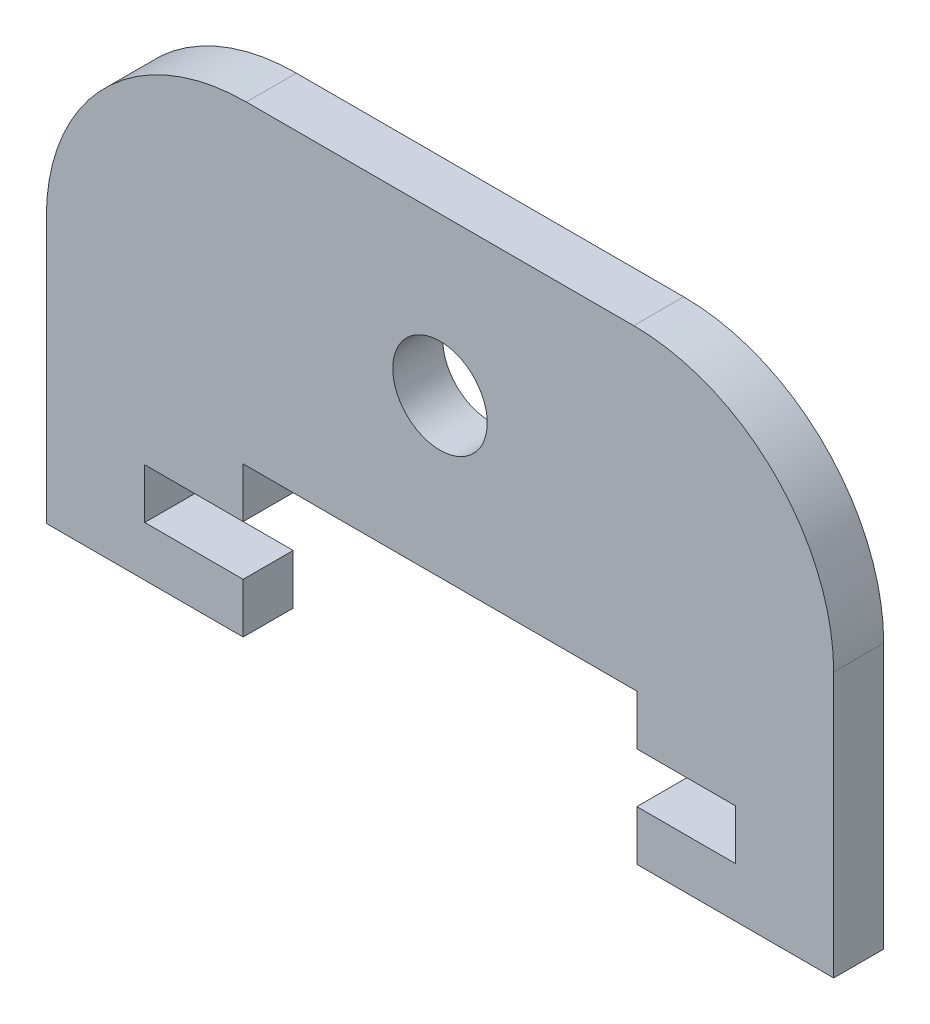
SolidWorks part; units mm, degrees
ref_plane "Front Plane" through (0, 0, 0) normal (0, 0, 1) x (1, 0, 0)
ref_plane "Top Plane" through (0, 0, 0) normal (0, 1, 0) x (1, 0, 0)
ref_plane "Right Plane" through (0, 0, 0) normal (1, 0, 0) x (0, 0, -1)
sketch "Sketch1" plane through (0, 0, 0) normal (0, 0, 1) x (1, 0, 0)
  line L0 (50, 40) -> (50, -11.8795) construction
  line L1 (25, 0) -> (75, 0)
  line L2 (0, 0) -> (0, 40)
  line L3 (0, 40) -> (100, 40)
  line L4 (100, 0) -> (100, 40)
  line L6 (0, 0) -> (0, -6.35)
  line L8 (25, 0) -> (25, -6.35)
  line L9 (75, 0) -> (75, -6.35)
  line L11 (100, 0) -> (100, -6.35)
  line L12 (0, -6.35) -> (0, -19.05)
  line L13 (0, -19.05) -> (25, -19.05)
  line L14 (25, -19.05) -> (25, -6.35)
  line L15 (75, -19.05) -> (75, -6.35)
  line L16 (100, -19.05) -> (75, -19.05)
  line L17 (100, -6.35) -> (100, -19.05)
  dimension "D1" = 100
  dimension "D2" = 6.35
  dimension "D3" = 40
  dimension "D4" = 25
  dimension "D5" = 6.35
  dimension "D6" = 12.7
extrude "Boss-Extrude1" add sketch "Sketch1" along normal blind 6.35
sketch "Sketch2" plane through (0, 0, 6.35) normal (0, 0, 1) x (1, 0, 0)
  line L0 (-10.2656, 2) -> (76.84, 2) construction
  line L2 (50, 40) -> (50, 0) construction
  line L3 (100, 40) -> (0, 40) construction
  line L4 (25, 0) -> (75, 0) construction
  circle A0 centre (50, 20) radius 6
  dimension "D3" = 12
  dimension "D1" = 20
extrude "Cut-Extrude1" cut sketch "Sketch2" against normal through all both and the other way through all
fillet "Fillet1" radius 25.4 2 edges at (100, 40, 3.175) (0, 40, 3.175)
sketch "Sketch3" plane through (0, 0, 6.35) normal (0, 0, 1) x (1, 0, 0)
  line L0 (50.038, 52.1218) -> (50.038, -31.1869) construction
  line L1 (75, -6.35) -> (87.5, -6.35)
  line L2 (25, 0) -> (25, -6.35) construction
  line L3 (25, -19.05) -> (25, 0) construction
  line L4 (25, -6.35) -> (12.5, -6.35)
  line L5 (12.5, -6.35) -> (12.5, -12.7)
  line L6 (12.5, -12.7) -> (25, -12.7)
  line L7 (25, -6.35) -> (25, -12.7)
  line L10 (75, 0) -> (75, -19.05) construction
  line L11 (87.5, -6.35) -> (87.5, -12.7)
  line L12 (87.5, -12.7) -> (75, -12.7)
  line L13 (75, -6.35) -> (75, -12.7)
  line L14 (25, 0) -> (75, 0) construction
  dimension "D5" = 6.35
  dimension "D1" = 6.35
  dimension "D2" = 12.5
  dimension "D3" = 6.35
  dimension "D4" = 50.038
  dimension "D6" = 6.35
  dimension "D7" = 12.5
extrude "Cut-Extrude2" cut sketch "Sketch3" against normal through all both and the other way through all
equation "\"Wheel Thickness\"= 1in"
equation "\"Wheel Diameter\"= 3in"
equation "\"Motor Rear Diameter\" = 36.2mm"
equation "\"Motor Front Diameter\" = 12mm"
equation "\"Material Thickness\" = .25in"
equation "\"Wheel Cutout Diameter\"= 2cm"
equation "\"Motor Mount Tab Thickness\" = 100mm"
equation "\"Motor Mount Tab Height\" = 40mm"
equation "\"D1@Sketch1\"=\"Motor Mount Tab Thickness\""
equation "\"D1@Boss-Extrude1\"=\"Material Thickness\""
equation "\"D2@Sketch1\"=\"Material Thickness\""
equation "\"D3@Sketch1\"=\"Motor Mount Tab Height\""
equation "\"D4@Sketch1\"=\"Motor Mount Tab Thickness\"/4"
equation "\"D3@Sketch2\"=\"Motor Front Diameter\""
equation "\"D5@Sketch1\"=\"Material Thickness\""
equation "\"D1@Sketch2\"=\"Motor Mount Tab Height\"/2"
equation "\"D6@Sketch1\"=\"Material Thickness\"*2"
equation "\"D1@Sketch3\"=\"Material Thickness\""
equation "\"D2@Sketch3\"=\"Motor Mount Tab Thickness\"/8"
equation "\"D3@Sketch3\"=\"Material Thickness\""
equation "\"D5@Sketch3\"=\"Material Thickness\""
equation "\"D6@Sketch3\"=\"Material Thickness\""
equation "\"D7@Sketch3\"=\"Motor Mount Tab Thickness\"/8"
